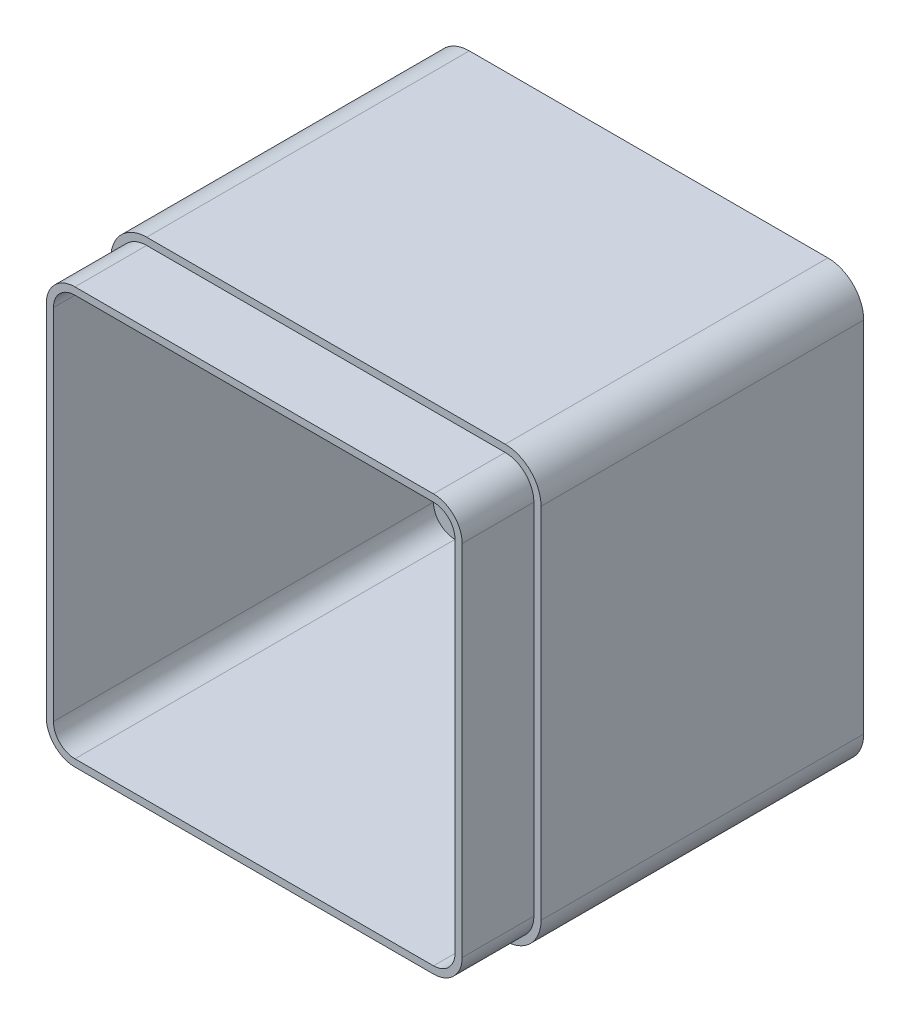
SolidWorks part; units mm, degrees
ref_plane "Front" through (0, 0, 0) normal (0, 0, 1) x (1, 0, 0)
ref_plane "Top" through (0, 0, 0) normal (0, 1, 0) x (1, 0, 0)
ref_plane "Right" through (0, 0, 0) normal (1, 0, 0) x (0, 0, -1)
sketch "Sketch1" plane through (0, 0, 0) normal (0, 0, 1) x (1, 0, 0)
  line L1 (0, 0) -> (120, 0)
  line L2 (0, 0) -> (0, 120)
  line L3 (0, 120) -> (120, 120)
  line L4 (120, 0) -> (120, 120)
  dimension "D1" = 120
  dimension "D2" = 120
extrude "Boss-Extrude1" add sketch "Sketch1" along normal blind 90
fillet "Fillet1" radius 10 4 edges at (0, 0, 45) (120, 0, 45) (0, 120, 45) (120, 120, 45)
shell "Shell1" thickness 4
sketch "Sketch3" plane through (0, 0, 90) normal (0, 0, 1) x (1, 0, 0)
  line L8 (0, 110) -> (0, 10)
  line L9 (10, 0) -> (110, 0)
  line L10 (120, 10) -> (120, 110)
  line L11 (110, 120) -> (10, 120)
  line L12 (0, 110) -> (0, 10)
  line L13 (10, 0) -> (110, 0)
  line L14 (120, 10) -> (120, 110)
  line L15 (110, 120) -> (10, 120)
  line L16 (110, 116) -> (10, 116) construction
  line L17 (4, 110) -> (4, 10) construction
  line L18 (110, 116) -> (10, 116)
  line L19 (4, 110) -> (4, 10)
  line L28 (2, 110) -> (2, 10)
  line L29 (10, 2) -> (110, 2)
  line L30 (118, 10) -> (118, 110)
  line L31 (110, 118) -> (10, 118)
  line L32 (2, 110) -> (2, 10)
  line L33 (10, 2) -> (110, 2)
  line L34 (118, 10) -> (118, 110)
  line L35 (110, 118) -> (10, 118)
  arc A8 (0, 10) -> (10, 0) centre (10, 10) ccw
  arc A9 (110, 0) -> (120, 10) centre (110, 10) ccw
  arc A10 (120, 110) -> (110, 120) centre (110, 110) ccw
  arc A11 (10, 120) -> (0, 110) centre (10, 110) ccw
  arc A12 (0, 10) -> (10, 0) centre (10, 10) ccw
  arc A13 (110, 0) -> (120, 10) centre (110, 10) ccw
  arc A14 (120, 110) -> (110, 120) centre (110, 110) ccw
  arc A15 (10, 120) -> (0, 110) centre (10, 110) ccw
  arc A16 (10, 116) -> (4, 110) centre (10, 110) ccw construction
  arc A17 (10, 116) -> (4, 110) centre (10, 110) ccw
  arc A26 (2, 10) -> (10, 2) centre (10, 10) ccw
  arc A27 (110, 2) -> (118, 10) centre (110, 10) ccw
  arc A28 (118, 110) -> (110, 118) centre (110, 110) ccw
  arc A29 (10, 118) -> (2, 110) centre (10, 110) ccw
  arc A30 (2, 10) -> (10, 2) centre (10, 10) ccw
  arc A31 (110, 2) -> (118, 10) centre (110, 10) ccw
  arc A32 (118, 110) -> (110, 118) centre (110, 110) ccw
  arc A33 (10, 118) -> (2, 110) centre (10, 110) ccw
  line M25 (4, 10) -> (4, 110)
  arc M26 (4, 110) -> (10, 116) centre (10, 110) cw
  line M27 (10, 116) -> (110, 116)
  arc M28 (110, 116) -> (116, 110) centre (110, 110) cw
  line M29 (116, 110) -> (116, 10)
  arc M30 (116, 10) -> (110, 4) centre (110, 10) cw
  line M31 (110, 4) -> (10, 4)
  arc M32 (10, 4) -> (4, 10) centre (10, 10) cw
  dimension "D1" = 0
  dimension "D2" = 2
extrude "Boss-Extrude2" add sketch "Sketch3" along normal blind 20 contours L35 A33 L32 A30 L33 A31 L34 A32 M32 M25 M26 M27 M28 M29 M30 M31
